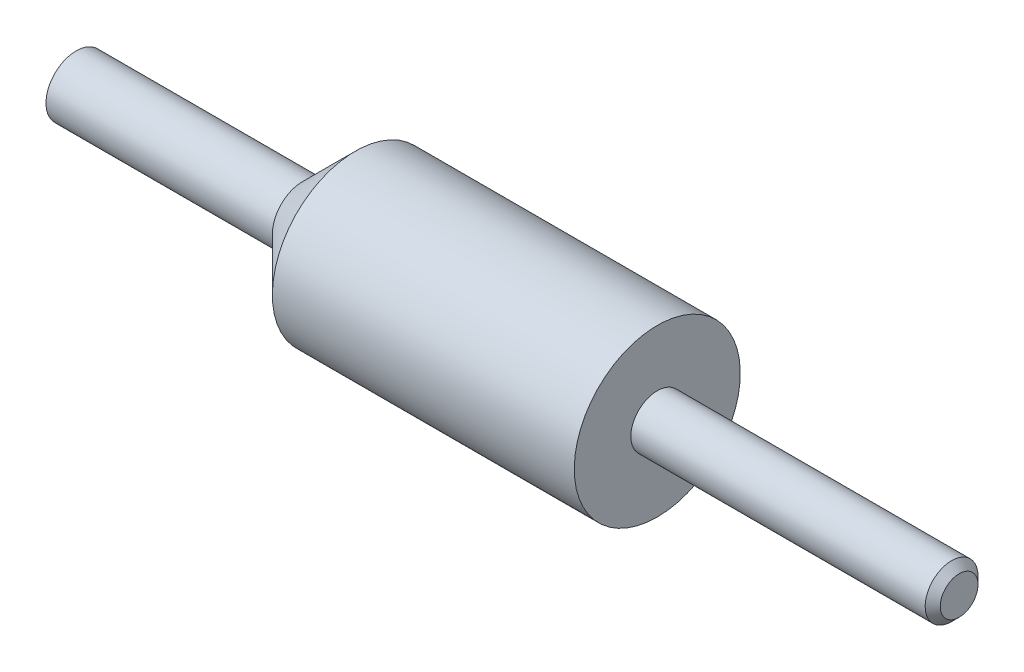
SolidWorks part; units mm, degrees
ref_plane "Front Plane" through (0, 0, 0) normal (0, 0, 1) x (1, 0, 0)
ref_plane "Top Plane" through (0, 0, 0) normal (0, 1, 0) x (1, 0, 0)
ref_plane "Right Plane" through (0, 0, 0) normal (1, 0, 0) x (0, 0, -1)
sketch "Sketch1" plane through (0, 0, 0) normal (0, 0, 1) x (1, 0, 0)
  line L0 (-58.5, 0) -> (0, 0)
  line L1 (0, 0) -> (0, 1.75)
  line L2 (0, 1.75) -> (-20, 1.75)
  line L3 (-20, 1.75) -> (-20, 5.5)
  line L4 (-20, 5.5) -> (-40, 5.5)
  line L5 (-40, 5.5) -> (-43.5, 2)
  line L6 (-43.5, 2) -> (-58.5, 2)
  line L7 (-58.5, 2) -> (-58.5, 0)
  point P3 (-38.0691, 4.2875)
  point P10 (-19.4834, 2)
  point P11 (-7.6172, 7.4327)
  point P12 (-7.0453, 2.2859)
  point P13 (-26.6653, 7.3938)
  point P14 (-30.2622, 2)
  point P15 (-59.2004, 0)
  dimension "D1" = 2
  dimension "D2" = 1.75
  dimension "D3" = 20
  dimension "D4" = 5.5
  dimension "D5" = 135
  dimension "D6" = 20
  dimension "D7" = 15
revolve "Revolve1" add sketch "Sketch1" angle 360 about L0
chamfer "Chamfer1" distance 0.5 angle 45 1 edges at (0, -1.75, 0)
